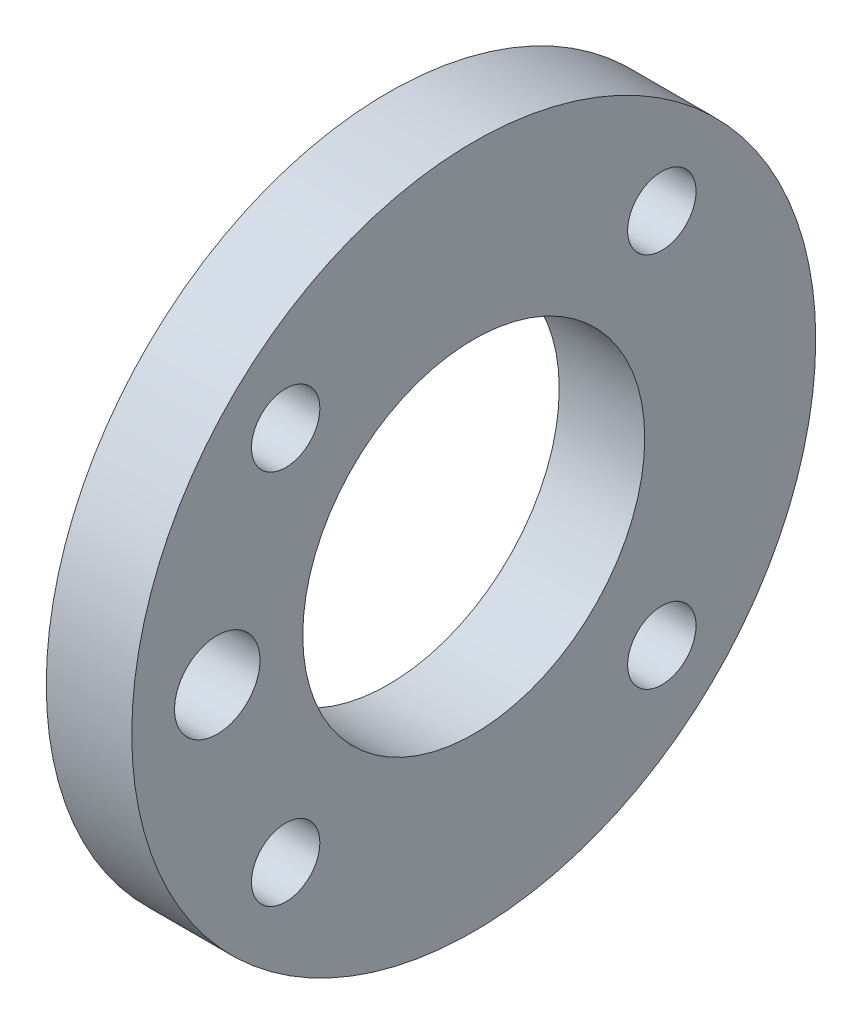
SolidWorks part; units mm, degrees
ref_plane "Front Plane" through (0, 0, 0) normal (0, 0, 1) x (1, 0, 0)
ref_plane "Top Plane" through (0, 0, 0) normal (0, 1, 0) x (1, 0, 0)
ref_plane "Right Plane" through (0, 0, 0) normal (1, 0, 0) x (0, 0, -1)
sketch "Sketch1" plane through (0, 0, 0) normal (1, 0, 0) x (0, 0, -1)
  line L1 (11, -11) -> (-11, -11) construction
  line L2 (11, -11) -> (11, 11) construction
  line L3 (11, 11) -> (-11, 11) construction
  line L4 (-11, -11) -> (-11, 11) construction
  line L5 (11, -11) -> (-11, 11) construction
  line L6 (11, 11) -> (-11, -11) construction
  circle A0 centre (0, 0) radius 20
  circle A1 centre (0, 0) radius 10
  circle A2 centre (-11, 11) radius 2
  circle A3 centre (11, 11) radius 2
  circle A4 centre (11, -11) radius 2
  circle A5 centre (-11, -11) radius 2
  circle A6 centre (-15, 0) radius 2.5
  dimension "D1" = 40
  dimension "D2" = 20
  dimension "D5" = 4
  dimension "D8" = 5
  dimension "D3" = 22
  dimension "D4" = 22
  dimension "D9" = 15
  dimension "D6" = 2
  dimension "D7" = 2
extrude "Boss-Extrude1" add sketch "Sketch1" along normal blind 5
